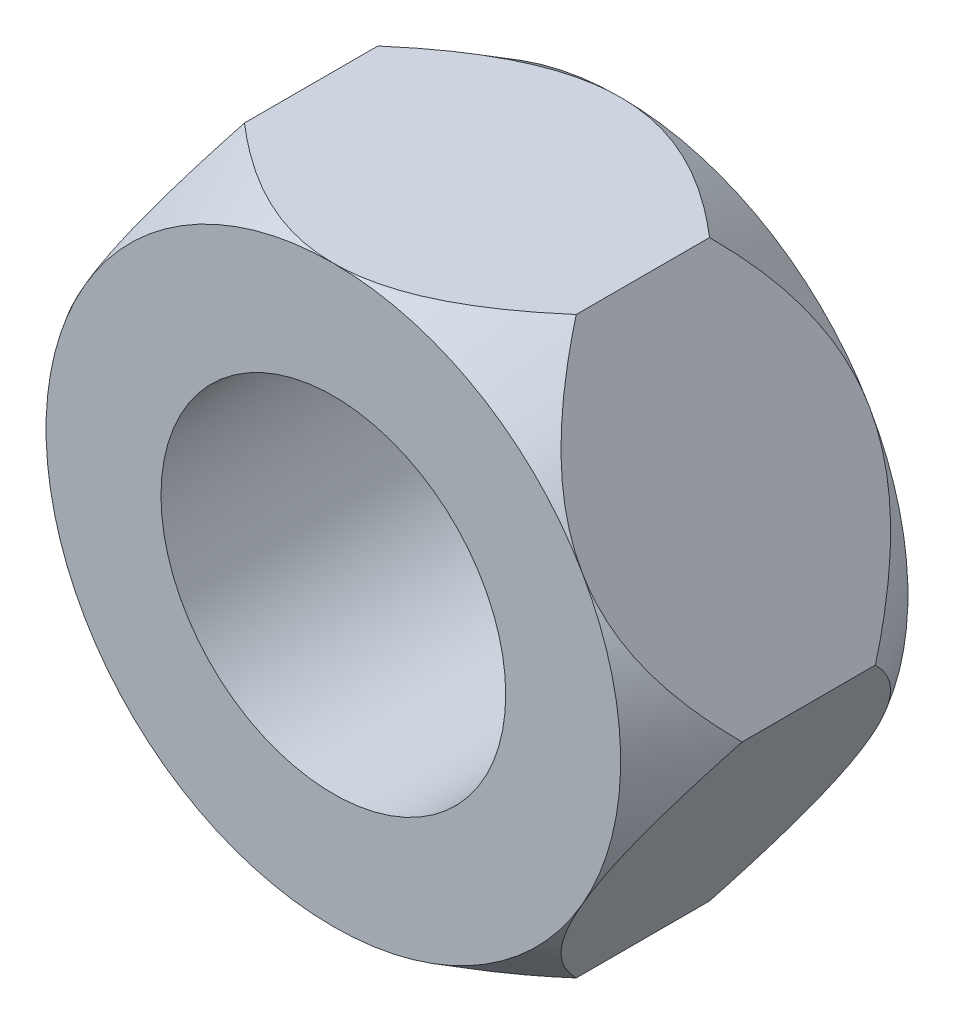
SolidWorks part; units mm, degrees
ref_plane "Front Plane" through (0, 0, 0) normal (0, 0, 1) x (1, 0, 0)
ref_plane "Top Plane" through (0, 0, 0) normal (0, 1, 0) x (1, 0, 0)
ref_plane "Right Plane" through (0, 0, 0) normal (1, 0, 0) x (0, 0, -1)
sketch "Croquis1" plane through (0, 0, 0) normal (0, 0, 1) x (1, 0, 0)
  line L1 (5.7735, 0) -> (2.8868, 5)
  line L2 (2.8868, 5) -> (-2.8868, 5)
  line L3 (-2.8868, 5) -> (-5.7735, 0)
  line L4 (-5.7735, 0) -> (-2.8868, -5)
  line L5 (-2.8868, -5) -> (2.8868, -5)
  line L6 (2.8868, -5) -> (5.7735, 0)
  circle A0 centre (0, 0) radius 5 construction
  circle A1 centre (0, 0) radius 3
  dimension "D1" = 5
extrude "Saliente-Extruir1" add sketch "Croquis1" along normal blind 5
sketch "Croquis2" plane through (0, 0, 5) normal (0, 0, 1) x (1, 0, 0)
  circle A0 centre (0, 0) radius 5
extrude "Cortar-Extruir1" cut sketch "Croquis2" against normal blind 5 draft 30 flip side to cut
sketch "Croquis3" plane through (0, 0, 0) normal (0, 0, -1) x (-1, 0, 0)
  circle A0 centre (0, 0) radius 5
extrude "Cortar-Extruir2" cut sketch "Croquis3" against normal blind 5 draft 30 flip side to cut
